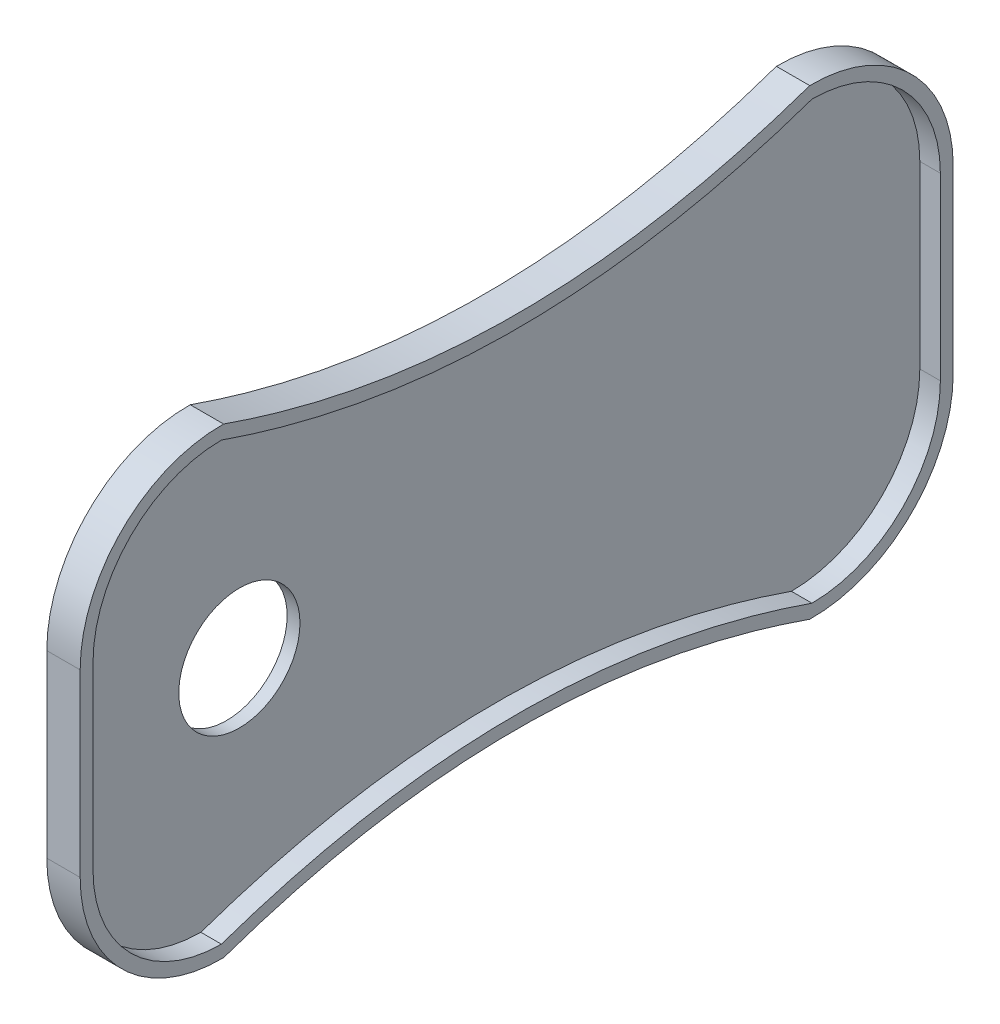
SolidWorks part; units mm, degrees
ref_plane "Alzado" through (0, 0, 0) normal (0, 0, 1) x (1, 0, 0)
ref_plane "Planta" through (0, 0, 0) normal (0, 1, 0) x (1, 0, 0)
ref_plane "Vista lateral" through (0, 0, 0) normal (1, 0, 0) x (0, 0, -1)
sketch "Croquis1" plane through (0, 0, 0) normal (1, 0, 0) x (0, 0, -1)
  line L2 (165, -35) -> (165, 35)
  line L4 (-165, -35) -> (-165, 35)
  line L5 (165, -85) -> (-165, 85) construction
  line L6 (165, 85) -> (-165, -85) construction
  arc A0 (-165, -35) -> (-115, -85) centre (-115, -35) ccw
  arc A1 (115, -85) -> (165, -35) centre (115, -35) ccw
  arc A2 (115, 85) -> (165, 35) centre (115, 35) cw
  arc A3 (-115, 85) -> (-165, 35) centre (-115, 35) ccw
  circle A5 centre (-100, 0) radius 23.6
  spline S0 degree 2 poles (-115, 85) (0, 45) (115, 85) knots 0 0 0 1 1 1
  spline S1 degree 2 poles (-115, -85) (0, -45) (115, -85) knots 0 0 0 1 1 1
  point P0 (0, 0)
  dimension "D3" = 50
  dimension "D5" = 47.2
  dimension "D1" = 330
  dimension "D2" = 170
  dimension "D6" = 20
  dimension "D7" = 20
  dimension "D9" = 100
extrude "Saliente-Extruir1" add sketch "Croquis1" along normal blind 8
shell "Vaciado1" thickness 5
sketch "Croquis2" plane through (8, 0, 0) normal (1, 0, 0) x (0, 0, -1)
  circle A0 centre (-100, 0) radius 23.6
extrude "Cortar-Extruir1" cut sketch "Croquis2" against normal blind 214
